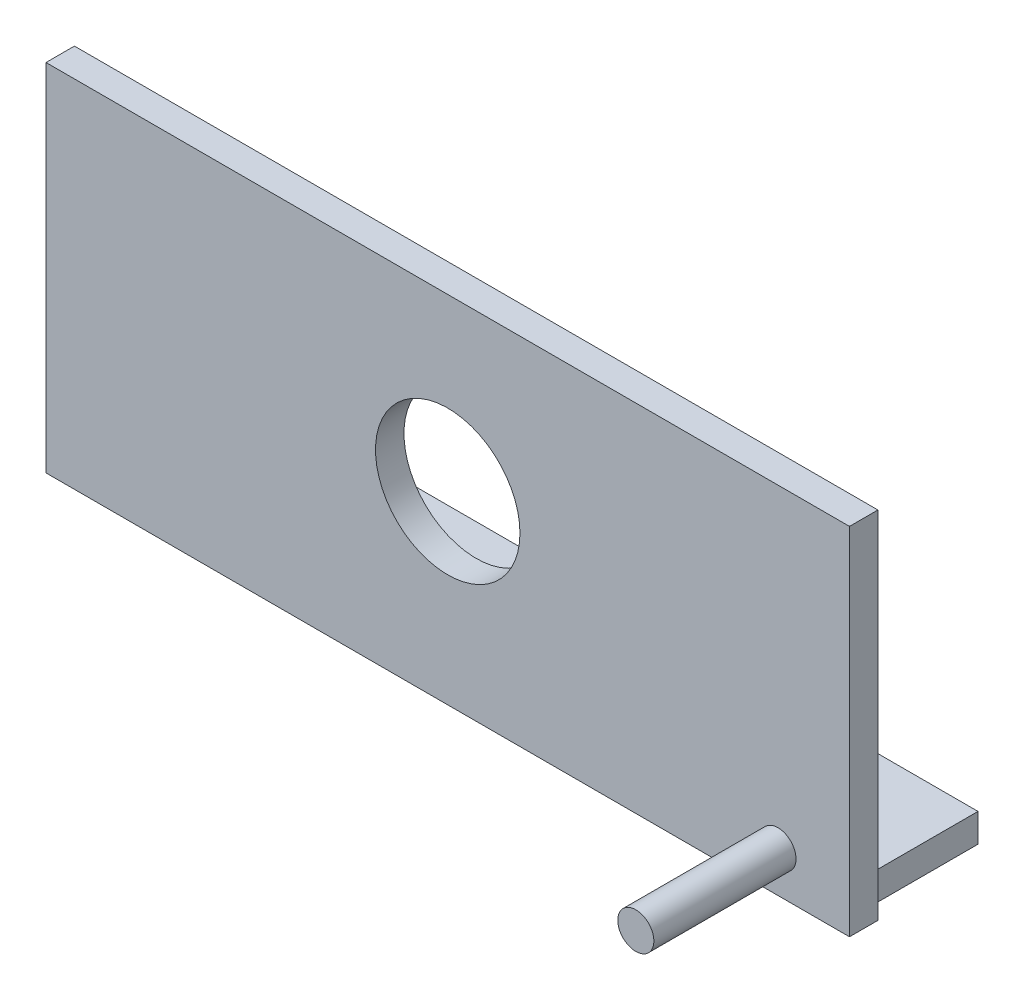
SolidWorks part; units mm, degrees
ref_plane "Alzado" through (0, 0, 0) normal (0, 0, 1) x (1, 0, 0)
ref_plane "Planta" through (0, 0, 0) normal (0, 1, 0) x (1, 0, 0)
ref_plane "Vista lateral" through (0, 0, 0) normal (1, 0, 0) x (0, 0, -1)
sketch "Croquis1" plane through (0, 0, 0) normal (0, 0, 1) x (1, 0, 0)
  line L0 (0, 0) -> (0, 60) construction
  line L4 (67.8398, 2.498) -> (34.641, 60)
  line L5 (34.641, 60) -> (-34.641, 60)
  line L6 (-34.641, 60) -> (-67.8398, 2.498)
  line L7 (-67.8398, 2.498) -> (67.8398, 2.498)
  line L8 (-28.4365, -60) -> (37.961, -60) [skipped]
  line L9 (51.9615, -30) -> (68.5609, -1.249) [skipped]
  line L10 (-66.1798, -5.3733) -> (-49.5804, -34.1242) [skipped]
  arc A0 (57.4477, 2.498) -> (-57.4477, 2.498) centre (0, 0) ccw construction
  circle A1 centre (0, 30) radius 12.7
  dimension "D1" = 25.4
  dimension "D2" = 60
extrude "Saliente-Extruir1" add sketch "Croquis1" along normal blind 5
sketch "Croquis3" plane through (0, 0, 5) normal (0, 0, 1) x (1, 0, 0)
  line L1 (-67.8398, 2.498) -> (67.8398, 2.498)
  line L2 (-67.8398, 2.498) -> (-67.8398, -2.502)
  line L3 (-67.8398, -2.502) -> (67.8398, -2.502)
  line L4 (67.8398, 2.498) -> (67.8398, -2.502)
  dimension "D1" = 5
extrude "Saliente-Extruir3" add sketch "Croquis3" against normal blind 25.4
sketch "Croquis4" plane through (0, 0, 5) normal (0, 0, 1) x (1, 0, 0)
  line L0 (58.0698, -2.502) -> (58.0698, 4.658) construction
  line L2 (-67.8398, -2.502) -> (67.8398, -2.502) construction
  line L3 (67.8398, -2.502) -> (67.8398, 2.498) construction
  circle A0 centre (58.0698, 4.658) radius 3.175
  dimension "D3" = 6.35
  dimension "D1" = 9.77
  dimension "D2" = 7.16
extrude "Saliente-Extruir4" add sketch "Croquis4" along normal blind 25
sketch "Croquis5" plane through (0, 0, 5) normal (0, 0, 1) x (1, 0, 0)
  line L0 (70.641, 60) -> (70.641, -2.502)
  line L1 (70.641, -2.502) -> (67.8398, -2.502)
  line L2 (0, -8.3046) -> (0, 26.7425) construction
  line L3 (67.8398, -2.502) -> (67.8398, 2.498)
  line L4 (-67.8398, -2.502) -> (-67.8398, 2.498)
  line L5 (34.641, 60) -> (70.641, 60)
  line L6 (-34.641, 60) -> (-67.8398, 2.498)
  line L8 (34.641, 60) -> (67.8398, 2.498)
  line L9 (-70.641, 60) -> (-70.641, -2.502)
  line L10 (-34.641, 60) -> (-70.641, 60)
  line L11 (-67.8398, -2.502) -> (-70.641, -2.502)
  dimension "D1" = 36
extrude "Saliente-Extruir5" add sketch "Croquis5" against normal up to surface (5 mm away) up to face at (0, 31.249, 0)
